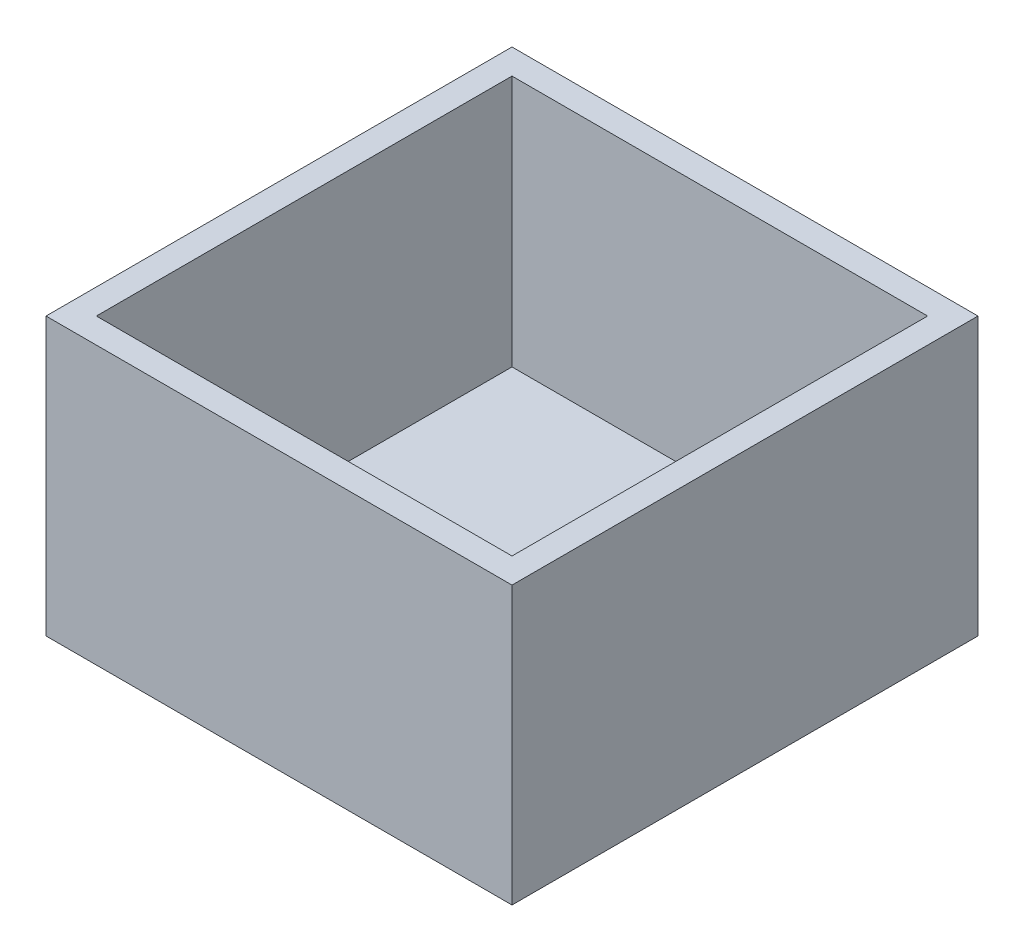
SolidWorks part; units mm, degrees
ref_plane "Front Plane" through (0, 0, 0) normal (0, 0, 1) x (1, 0, 0)
ref_plane "Top Plane" through (0, 0, 0) normal (0, 1, 0) x (1, 0, 0)
ref_plane "Right Plane" through (0, 0, 0) normal (1, 0, 0) x (0, 0, -1)
sketch "Sketch1" plane through (0, 0, 0) normal (0, 1, 0) x (1, 0, 0)
  line L1 (0, 0) -> (82.5, 0) construction
  line L2 (0, 0) -> (0, -82.5) construction
  line L3 (0, -82.5) -> (82.5, -82.5) construction
  line L4 (82.5, 0) -> (82.5, -82.5) construction
sketch "Sketch2" plane through (0, 0, 0) normal (0, 1, 0) x (1, 0, 0)
  line L0 (41.25, 0) -> (41.25, 5) construction
  line L1 (-5, 5) -> (87.5, 5)
  line L2 (-5, 5) -> (-5, -87.5)
  line L3 (-5, -87.5) -> (87.5, -87.5)
  line L4 (87.5, 5) -> (87.5, -87.5)
  line L5 (0, 0) -> (82.5, 0) construction
  line L6 (82.5, -41.25) -> (87.5, -41.25) construction
  line L7 (82.5, 0) -> (82.5, -82.5) construction
  line L8 (0, -41.25) -> (-5, -41.25) construction
  line L9 (0, 0) -> (0, -82.5) construction
  line L10 (41.25, -82.5) -> (41.25, -87.5) construction
  line L11 (0, -82.5) -> (82.5, -82.5) construction
extrude "Boss-Extrude1" add sketch "Sketch2" along normal blind 55
sketch "Sketch3" plane through (0, 55, 0) normal (0, 1, 0) x (1, 0, 0)
  line L1 (0, 0) -> (82.5, 0)
  line L2 (0, 0) -> (0, -82.5)
  line L3 (0, -82.5) -> (82.5, -82.5)
  line L4 (82.5, 0) -> (82.5, -82.5)
extrude "Cut-Extrude1" cut sketch "Sketch3" against normal blind 50
